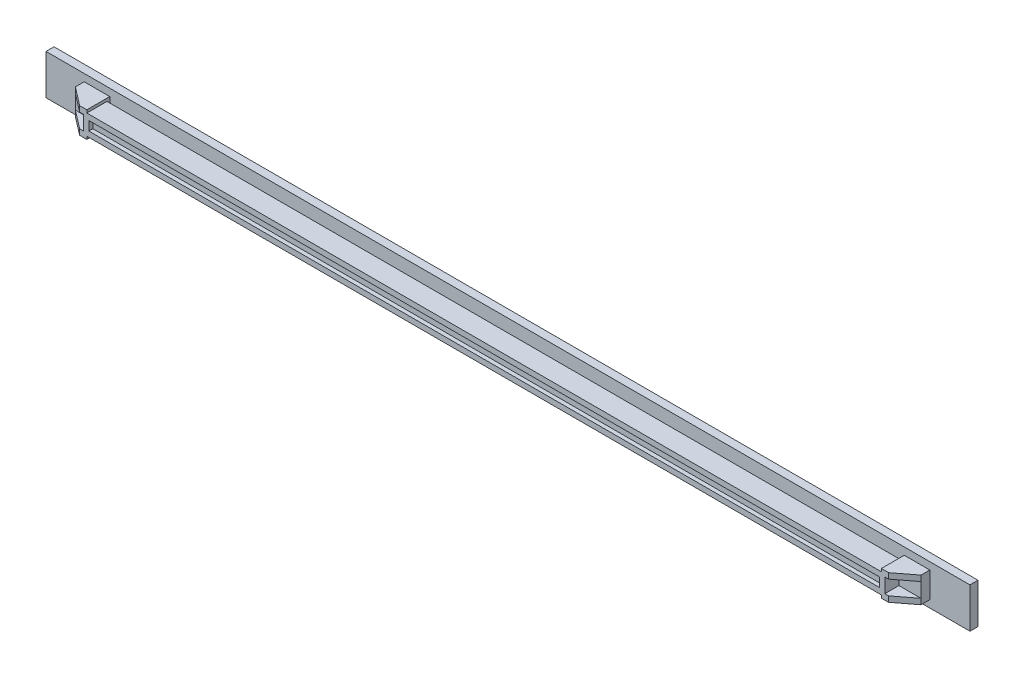
SolidWorks part; units mm, degrees
ref_plane "Front Plane" through (0, 0, 0) normal (0, 0, 1) x (1, 0, 0)
ref_plane "Top Plane" through (0, 0, 0) normal (0, 1, 0) x (1, 0, 0)
ref_plane "Right Plane" through (0, 0, 0) normal (1, 0, 0) x (0, 0, -1)
sketch "Sketch1" plane through (0, 0, 0) normal (0, 0, 1) x (1, 0, 0)
  line L1 (0, 0) -> (1000, 0)
  line L2 (0, 0) -> (0, 25)
  line L3 (0, 25) -> (1000, 25)
  line L4 (1000, 0) -> (1000, 25)
  dimension "D1" = 1000
  dimension "D2" = 25
extrude "Boss-Extrude1" add sketch "Sketch1" along normal blind 25
sketch "Sketch2" plane through (0, 0, 25) normal (0, 0, 1) x (1, 0, 0)
  line L0 (6.8, 18.2) -> (6.8, 6.8)
  line L1 (6.8, 6.8) -> (993.2, 6.8)
  line L2 (993.2, 6.8) -> (993.2, 18.2)
  line L3 (993.2, 18.2) -> (6.8, 18.2)
  line L4 (0, 25) -> (0, 0)
  line L5 (0, 0) -> (1000, 0)
  line L6 (1000, 0) -> (1000, 25)
  line L7 (1000, 25) -> (0, 25)
  line L8 (0, 25) -> (0, 0)
  line L9 (0, 0) -> (1000, 0)
  line L10 (1000, 0) -> (1000, 25)
  line L11 (1000, 25) -> (0, 25)
  dimension "D1" = 0
  dimension "D2" = 6.8
extrude "Cut-Extrude2" cut sketch "Sketch2" against normal blind 5 contours L0 L1 L2 L3
ref_plane "Plane1" through (500, 0, 0) normal (1, 0, 0) x (0, 0, -1)
sketch "Sketch4" plane through (6.8, 0, 0) normal (1, 0, 0) x (0, 0, -1)
  line L4 (0, 0) -> (0, 25)
  line L5 (-25, 0) -> (0, 0)
  line L6 (-25, 25) -> (-25, 0)
  line L7 (0, 25) -> (-25, 25)
  line L8 (0, 0) -> (0, 25)
  line L9 (-25, 0) -> (0, 0)
  line L10 (-25, 25) -> (-25, 0)
  line L11 (0, 25) -> (-25, 25)
  line L16 (3.5, -3.5) -> (3.5, 28.5)
  line L17 (-28.5, -3.5) -> (3.5, -3.5)
  line L18 (-28.5, 28.5) -> (-28.5, -3.5)
  line L19 (3.5, 28.5) -> (-28.5, 28.5)
  line L20 (3.5, -3.5) -> (3.5, 28.5)
  line L21 (-28.5, -3.5) -> (3.5, -3.5)
  line L22 (-28.5, 28.5) -> (-28.5, -3.5)
  line L23 (3.5, 28.5) -> (-28.5, 28.5)
  dimension "D1" = 0
  dimension "D2" = 3.5
extrude "Boss-Extrude2" add sketch "Sketch4" against normal up to surface (6.8 mm away) separate body up to face at (0, 12.5, 12.5)
sketch "Sketch5" plane through (0, 0, 0) normal (-1, 0, 0) x (0, 0, 1)
  line L4 (-3.5, -3.5) -> (28.5, -3.5) construction
  line L5 (28.5, -3.5) -> (28.5, 28.5) construction
  line L6 (28.5, 28.5) -> (-3.5, 28.5) construction
  line L7 (-3.5, 28.5) -> (-3.5, -3.5) construction
  line L12 (-3.5, -3.5) -> (28.5, -3.5)
  line L13 (28.5, -3.5) -> (28.5, 28.5)
  line L14 (28.5, 28.5) -> (-3.5, 28.5)
  line L15 (-3.5, 28.5) -> (-3.5, -3.5)
extrude "Boss-Extrude3" add sketch "Sketch5" along normal blind 25
sketch "Sketch6" plane through (0, 0, 28.5) normal (0, 0, 1) x (1, 0, 0)
  line L0 (-25, -3.5) -> (-25, 28.5) construction
  line L1 (-25, 21.5) -> (2.4481, 21.5)
  line L2 (-25, 21.5) -> (-25, 3.5)
  line L3 (-25, 3.5) -> (2.4481, 3.5)
  line L4 (2.4481, 21.5) -> (2.4481, 3.5)
  line L5 (6.8, 12.5) -> (4.7005, 12.5) construction
  line L6 (6.8, 28.5) -> (6.8, -3.5) construction
  line L7 (-25, -3.5) -> (6.8, -3.5) construction
  dimension "D1" = 18
  dimension "D2" = 7
extrude "Cut-Extrude3" cut sketch "Sketch6" against normal blind 21
sketch "Sketch7" plane through (0, -3.5, 0) normal (0, -1, 0) x (1, 0, 0)
  line L0 (-25, 28.5) -> (2.4481, 28.5) construction
  line L3 (-25, 7.5) -> (-25, 28.5) construction
  line L6 (6.8, 28.5) -> (-25, 28.5) construction
  line L7 (-25, 28.5) -> (-25, -3.5) construction
  line L9 (-25, 28.5) -> (2.4481, 28.5)
  line L12 (-25, 7.5) -> (-25, 28.5)
  line L15 (2.4481, 28.5) -> (-25, 28.5)
  line L16 (-25, 28.5) -> (-25, 7.5)
  line L18 (2.4481, 28.5) -> (-25, 7.5)
  line M3 (6.8, 28.5) -> (-25, 28.5)
  line M4 (-25, 28.5) -> (-25, -3.5)
extrude "Cut-Extrude4" cut sketch "Sketch7" against normal blind 43 contours L18 M3 M4
sketch "Sketch8" plane through (2.4481, 0, 0) normal (-1, 0, 0) x (0, 0, 1)
  line L0 (20, 6.8) -> (25, 6.8) construction
  line L1 (20, 18.2) -> (25, 18.2) construction
  line L2 (25, 25) -> (25, 18.2) construction
  line L3 (20, 18.2) -> (20, 6.8) construction
  line L4 (25, 6.8) -> (25, 0) construction
  line L5 (20, 6.8) -> (23, 6.8)
  line L6 (20, 18.2) -> (23, 18.2)
  line L7 (25, 30.7464) -> (25, 20.2)
  line L8 (20, 18.2) -> (20, 6.8)
  line L9 (25, 4.8) -> (25, -5.0208)
  line L10 (25, 30.7464) -> (31.9916, 30.7464)
  line L11 (31.9916, 30.7464) -> (31.9916, -5.0208)
  line L12 (31.9916, -5.0208) -> (25, -5.0208)
  arc A0 (23, 6.8) -> (25, 4.8) centre (23, 4.8) cw
  arc A1 (23, 18.2) -> (25, 20.2) centre (23, 20.2) ccw
  dimension "D1" = 2
extrude "Cut-Extrude5" cut sketch "Sketch8" against normal blind 413 and the other way blind 43
ref_plane "Plane2" through (501.2241, 0, 0) normal (1, 0, 0) x (0, 0, -1)
mirror "Mirror6" about plane through (501.2241, 0, 0) normal (1, 0, 0) of bodies 113 114
sketch "Sketch10" plane through (1027.4481, 0, 0) normal (1, 0, 0) x (0, 0, -1)
  line L1 (3.5, 37.5) -> (13.5, 37.5)
  line L2 (3.5, 37.5) -> (3.5, -12.5)
  line L3 (3.5, -12.5) -> (13.5, -12.5)
  line L4 (13.5, 37.5) -> (13.5, -12.5)
  line L5 (-7.5, 12.5) -> (34.5, 12.5) construction
  line L6 (-7.5, 21.5) -> (-7.5, 3.5) construction
  line L7 (3.5, 28.5) -> (3.5, -3.5) construction
  point P9 (13.5, 12.5)
  dimension "D1" = 10
  dimension "D2" = 50
extrude "Boss-Extrude5" add sketch "Sketch10" against normal blind 1100 and the other way blind 50 separate body
